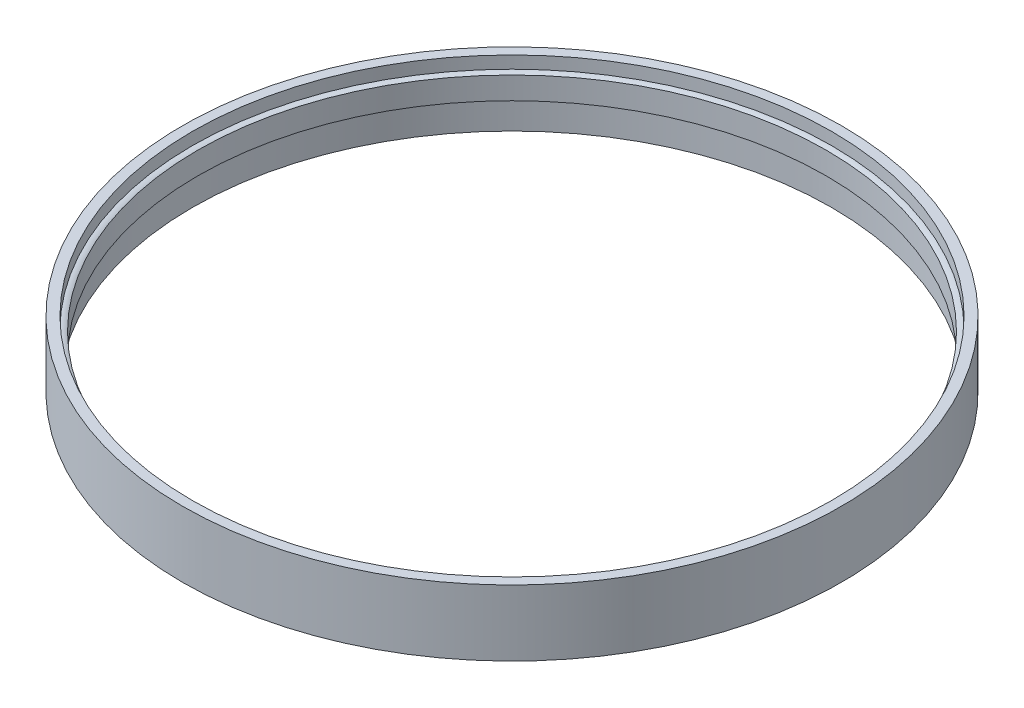
SolidWorks part; units mm, degrees
ref_plane "Plan de face" through (0, 0, 0) normal (0, 0, 1) x (1, 0, 0)
ref_plane "Plan de dessus" through (0, 0, 0) normal (0, 1, 0) x (1, 0, 0)
ref_plane "Plan de droite" through (0, 0, 0) normal (1, 0, 0) x (0, 0, -1)
sketch "Esquisse1" plane through (0, 0, 0) normal (0, 0, 1) x (1, 0, 0)
  line L0 (0, 0) -> (0, 22.5558) construction
  line L1 (-40, 8) -> (-40, 0)
  line L2 (-38.8, 8) -> (-38.8, 6.5)
  line L3 (-40, 8) -> (-38.8, 8)
  line L4 (-40, 0) -> (-38.8, 0)
  line L5 (-38.15, 6.3519) -> (-38.15, 3.6481)
  line L6 (-38.8, 3.5) -> (-38.8, 0)
  arc A0 (-38.15, 6.3519) -> (-38.8, 6.5) centre (-38.8, 5) ccw
  arc A1 (-38.8, 3.5) -> (-38.15, 3.6481) centre (-38.8, 5) ccw
  point P11 (-38.15, 7.3151)
  dimension "D1" = 40
  dimension "D3" = 3
  dimension "D6" = 3
  dimension "D2" = 38.8
  dimension "D4" = 38.15
  dimension "D5" = 8
revolve "Révolution1" add sketch "Esquisse1" angle 360 about L0
